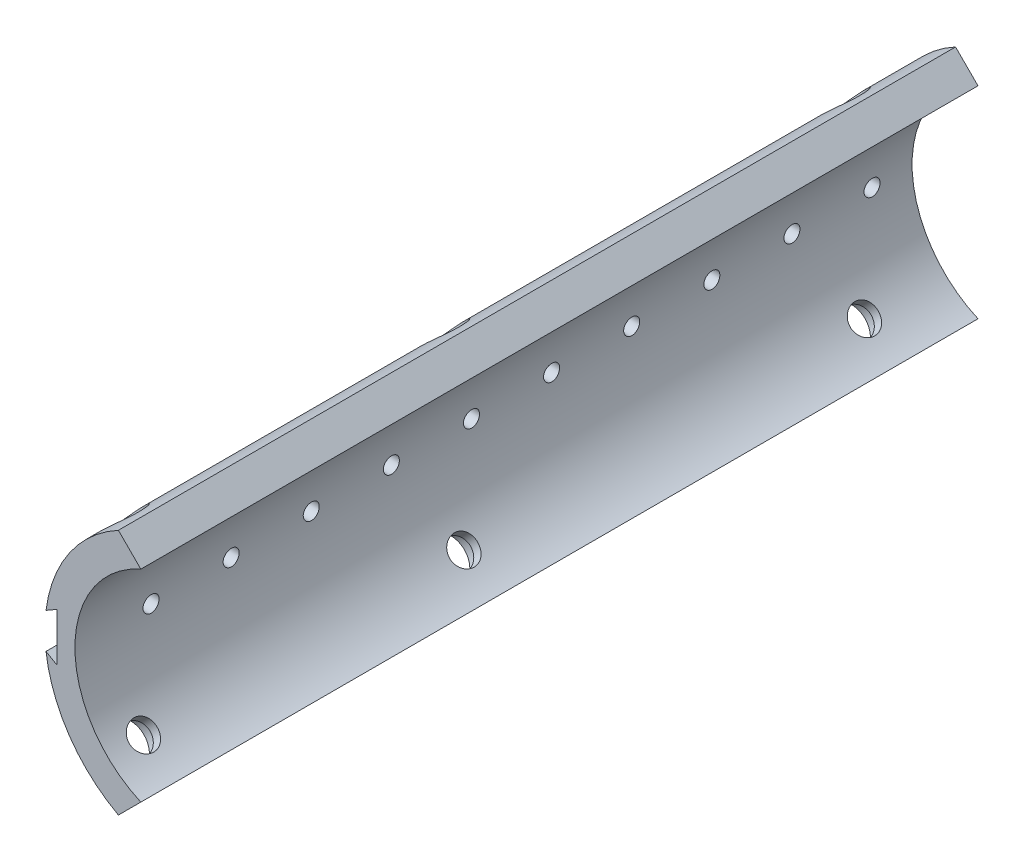
SolidWorks part; units mm, degrees
ref_plane "前视基准面" through (0, 0, 0) normal (0, 0, 1) x (1, 0, 0)
ref_plane "上视基准面" through (0, 0, 0) normal (0, 1, 0) x (1, 0, 0)
ref_plane "右视基准面" through (0, 0, 0) normal (1, 0, 0) x (0, 0, -1)
sketch "草图1" plane through (0, 0, 0) normal (0, 0, 1) x (1, 0, 0)
  circle A0 centre (0, 0) radius 27.5
  circle A1 centre (0, 0) radius 35
  dimension "D1" = 55
  dimension "D2" = 70
extrude "凸台-拉伸1" add sketch "草图1" along normal blind 209
sketch "草图2" plane through (0, 0, 0) normal (0, 0, -1) x (-1, 0, 0)
  line L0 (16.646, 30.7882) -> (-38.2625, -24.1204)
  line L1 (38.5, 0) -> (-38.5, 0) construction
  circle A0 centre (0, 0) radius 35 construction
  point P4 (-42.5283, -19.8442)
  dimension "D1" = 45
  dimension "D2" = 10
extrude "切除-拉伸1" cut sketch "草图2" against normal blind 209 and the other way through all flip side to cut
mirror "镜向1" about plane through (0, 0, 0) normal (0, 1, 0) of "切除-拉伸1"
sketch "草图3" plane through (0, 0, 0) normal (0, 0, -1) x (-1, 0, 0)
  line L1 (32, -6) -> (32, 6)
  line L2 (13.1763, 0) -> (-13.1763, 0) construction
  line L3 (32, 6) -> (42.3923, 0)
  line L4 (32, -6) -> (42.3923, 0)
  arc A3 (11.0432, -25.1853) -> (11.0432, 25.1853) centre (0, 0) ccw construction
  point P0 (32, 0)
  dimension "D1" = 12
  dimension "D2" = 120
  dimension "D3" = 60
  dimension "D4" = 4.5
extrude "切除-拉伸2" cut sketch "草图3" against normal blind 209
sketch "草图4" plane through (-32, 0, 0) normal (-1, 0, 0) x (0, 0, 1)
  line L0 (209, 0) -> (190, 0) construction
  line L1 (209, 6) -> (209, -6) construction
  line L2 (13.0214, 0) -> (-13.0214, 0) construction
  point P8 (190, 0)
  dimension "D1" = 19
hole_wizard "Ø4.0mm 暗销孔1" positions "草图4" profile "草图5" hole size "Ø4.0" standard "GB" end condition up to next
sketch "草图5" plane through (-32, 0, 190) normal (0, 1, 0) x (0, 0, 1)
  line L0 (0, 0) -> (0, 4.5)
  line L1 (0, 4.5) -> (2, 4.5)
  line L2 (2, 4.5) -> (2, 0)
  line L5 (2, 0) -> (0, 0)
  line L11 (0, -6.35) -> (0, 107.95) construction
  dimension "通孔孔直径" = 4
  dimension "通孔孔深度" = 4.5
pattern_linear "阵列(线性)1" count 10 spacing 20 along (0, 0, -1) of "Ø4.0mm 暗销孔1"
ref_plane "基准面1" through (0, 0, 20) normal (0, 0, 1) x (1, 0, 0)
hole_wizard "孔1" positions "3D草图1" profile "草图7" legacy end condition up to next
sketch3d "3D草图1"
  line L0 (-24.7487, 24.7487, 20) -> (0, 0, 20) construction
  line L1 (0, 0, 20) -> (-15.8955, 0, 20) construction
  point P0 (-24.7487, 24.7487, 20)
  point P4 (0, 0, 0)
  dimension "D1" = 45
sketch "草图7" plane through (-24.7487, 24.7487, 20) normal (0, 0, 1) x (-0.7071, -0.7071, 0)
  line L0 (0, 0) -> (0, 7.5)
  line L1 (0, 7.5) -> (3.5, 7.5)
  line L2 (3.5, 7.5) -> (3.5, 5)
  line L3 (3.5, 5) -> (5.5, 5)
  line L4 (5.5, 5) -> (5.5, 0)
  line L5 (5.5, 0) -> (0, 0)
  line L6 (0, 110) -> (0, -10) construction
  dimension "直径" = 7
  dimension "深度" = 7.5
  dimension "柱坑直径" = 11
  dimension "柱坑深度" = 5
pattern_circular "阵列(圆周)1" count 2 every 90 about axis through (0, 0, 209) along (0, 0, -1) of "孔1"
pattern_linear "阵列(线性)2" count 2 spacing 100 along (0, 0, 1) of "阵列(圆周)1", "孔1"
pattern_linear "阵列(线性)3" count 2 spacing 180 along (0, 0, 1) of "阵列(圆周)1", "孔1"
